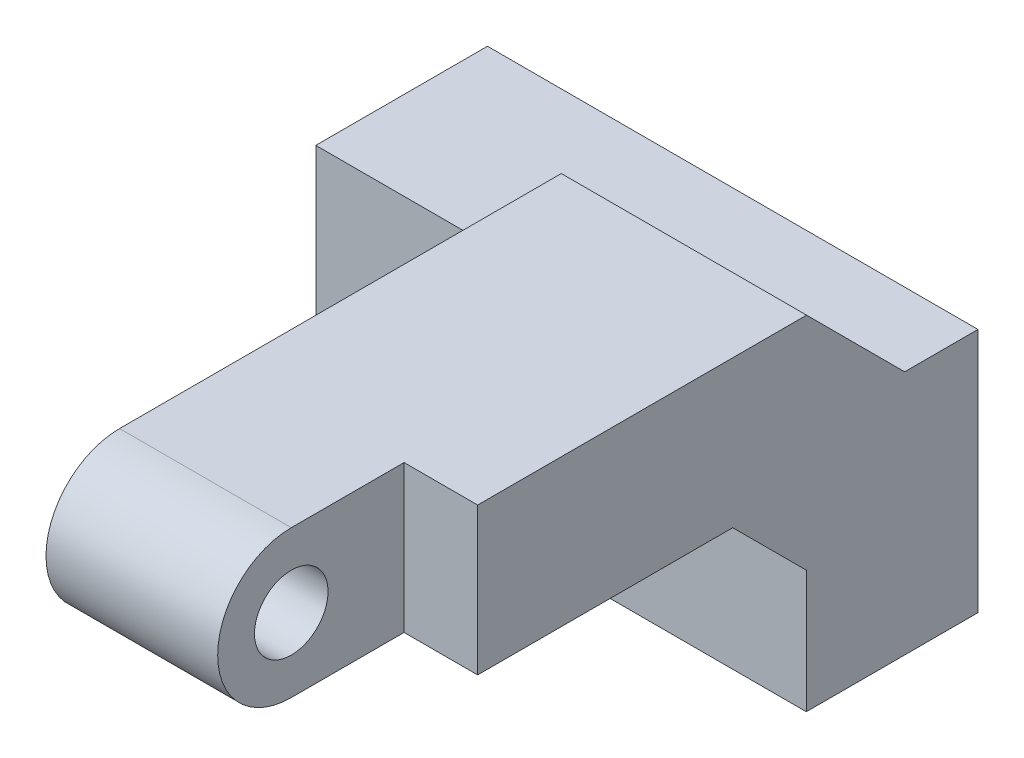
SolidWorks part; units mm, degrees
ref_plane "Plan de face" through (0, 0, 0) normal (0, 0, 1) x (1, 0, 0)
ref_plane "Plan de dessus" through (0, 0, 0) normal (0, 1, 0) x (1, 0, 0)
ref_plane "Plan de droite" through (0, 0, 0) normal (1, 0, 0) x (0, 0, -1)
sketch "Esquisse1" plane through (0, 0, 0) normal (0, 1, 0) x (1, 0, 0)
  line L0 (-10, 0) -> (10, 0) construction
  line L1 (-10, -3.5) -> (10, -3.5)
  line L2 (-10, -3.5) -> (-10, 3.5)
  line L3 (-10, 3.5) -> (10, 3.5)
  line L4 (10, -3.5) -> (10, 3.5)
  dimension "D1" = 20
  dimension "D2" = 7
extrude "Boss.-Extru.1" add sketch "Esquisse1" along normal blind 10
ref_plane "Plan1" through (0, 0, 0) normal (1, 0, 0) x (0, 0, -1)
sketch "Esquisse2" plane through (0, 0, 0) normal (1, 0, 0) x (0, 0, -1)
  line L0 (-3.5, 5) -> (-3.5, 10)
  line L1 (0.5103, 10) -> (-3.4897, 14)
  line L9 (-3.5, 10) -> (-3.5, 0) construction
  line L11 (-6.5, 8) -> (-21.5, 8)
  line L12 (-21.5, 14) -> (-3.4897, 14)
  line L14 (-6.5, 8) -> (-3.5, 5)
  line L15 (-3.5, 10) -> (3.5, 10) construction
  line L16 (-3.5, 10) -> (0.5103, 10)
  arc A2 (-21.5, 14) -> (-21.5, 8) centre (-21.5, 11) ccw
  dimension "D2" = 3
  dimension "D1" = 18
  dimension "D3" = 1
  dimension "D4" = 5
  dimension "D5" = 4.0103
  dimension "D6" = 45
extrude "Boss.-Extru.2" add sketch "Esquisse2" along normal blind 10
sketch "Esquisse3" plane through (0, 14, 0) normal (0, 1, 0) x (1, 0, 0)
  line L0 (10, -21.5) -> (0, -21.5) construction
  line L1 (10, -26.1) -> (7, -26.1)
  line L2 (10, -26.1) -> (10, -16.9)
  line L3 (10, -16.9) -> (7, -16.9)
  line L4 (7, -26.1) -> (7, -16.9)
  line L5 (10, -21.5) -> (0, -21.5) construction
  line L6 (10, -3.4897) -> (10, -21.5) construction
  dimension "D1" = 3
  dimension "D2" = 4.6
extrude "Enlèv. mat.-Extru.1" cut sketch "Esquisse3" against normal through all
sketch "Esquisse4" plane through (0, 0, 0) normal (-1, 0, 0) x (0, 0, 1)
  circle A0 centre (21.5, 11) radius 1.5
  dimension "D1" = 3
extrude "Enlèv. mat.-Extru.2" cut sketch "Esquisse4" against normal through all
sketch "Esquisse7" plane through (0, 0, 3.5) normal (0, 0, 1) x (1, 0, 0)
  line L0 (0, 0) -> (0, 4) construction
  line L1 (-10, 0) -> (10, 0) construction
  circle A0 centre (0, 4) radius 1.5
  dimension "D1" = 3
  dimension "D2" = 4
extrude "Enlèv. mat.-Extru.4" cut sketch "Esquisse7" against normal through all both and the other way through all
sketch "Esquisse5" plane through (0, 0, 3.5) normal (0, 0, 1) x (1, 0, 0)
  line L0 (0, -7.7) -> (0, 7.7) construction
  line L1 (-1.5877, 6.75) -> (-3.1754, 4)
  line L2 (-3.1754, 4) -> (-1.5877, 1.25)
  line L3 (-1.5877, 1.25) -> (1.5877, 1.25)
  line L4 (1.5877, 1.25) -> (3.1754, 4)
  line L5 (3.1754, 4) -> (1.5877, 6.75)
  line L6 (1.5877, 6.75) -> (-1.5877, 6.75)
  line L7 (-10, 0) -> (10, 0) construction
  circle A0 centre (0, 4) radius 2.75 construction
  dimension "D1" = 5.5
  dimension "D2" = 4
extrude "Enlèv. mat.-Extru.3" cut sketch "Esquisse5" against normal blind 3.5 and the other way through all
